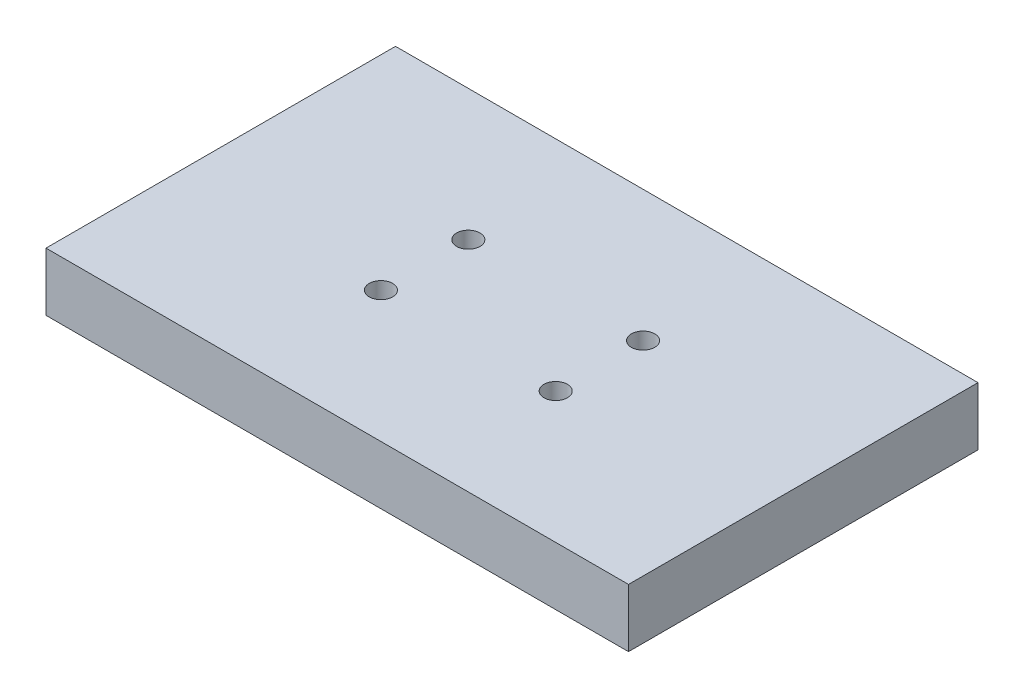
SolidWorks part; units mm, degrees
ref_plane "Front Plane" through (0, 0, 0) normal (0, 0, 1) x (1, 0, 0)
ref_plane "Top Plane" through (0, 0, 0) normal (0, 1, 0) x (1, 0, 0)
ref_plane "Right Plane" through (0, 0, 0) normal (1, 0, 0) x (0, 0, -1)
sketch "Sketch1" plane through (0, 0, 0) normal (0, 1, 0) x (1, 0, 0)
  line L1 (0, 0) -> (-127, 0)
  line L2 (0, 0) -> (0, 76.2)
  line L3 (0, 76.2) -> (-127, 76.2)
  line L4 (-127, 0) -> (-127, 76.2)
  dimension "D1" = 127
  dimension "D2" = 76.2
extrude "Boss-Extrude1" add sketch "Sketch1" along normal blind 12.7
sketch "Sketch3" plane through (0, 12.7, 0) normal (0, 1, 0) x (1, 0, 0)
  line L0 (-127, 38.1) -> (0, 38.1) construction
  line L1 (-127, 76.2) -> (-127, 0) construction
  line L2 (0, 0) -> (0, 76.2) construction
  line L3 (-63.5, 76.2) -> (-63.5, 0) construction
  line L4 (0, 76.2) -> (-127, 76.2) construction
  line L5 (-127, 0) -> (0, 0) construction
  line L7 (-82.55, 47.625) -> (-44.45, 47.625)
  line L8 (-82.55, 47.625) -> (-82.55, 28.575)
  line L9 (-82.55, 28.575) -> (-44.45, 28.575)
  line L10 (-44.45, 47.625) -> (-44.45, 28.575)
  line L11 (-82.55, 47.625) -> (-44.45, 28.575) construction
  line L12 (-82.55, 28.575) -> (-44.45, 47.625) construction
  point P12 (-63.5, 38.1)
  dimension "D1" = 19.05
  dimension "D2" = 38.1
hole_wizard "#7 (0.201) Diameter Hole1" positions "Sketch7" profile "Sketch8" hole size "#7" standard "ANSI Inch" end condition up to next
sketch "Sketch7" plane through (0, 12.7, 0) normal (0, 1, 0) x (1, 0, 0)
  point P0 (-82.55, 47.625)
  point P3 (-82.55, 28.575)
  point P6 (-44.45, 28.575)
  point P9 (-44.45, 47.625)
sketch "Sketch8" plane through (-82.55, 12.7, -47.625) normal (1, 0, 0) x (0, 0, 1)
  line L0 (0, 0) -> (0, 12.7)
  line L1 (0, 12.7) -> (2.5527, 12.7)
  line L2 (2.5527, 12.7) -> (2.5527, 0)
  line L5 (2.5527, 0) -> (0, 0)
  line L11 (0, -6.35) -> (0, 107.95) construction
  dimension "Thru Hole Dia." = 5.1054
  dimension "Thru Hole Depth" = 12.7
